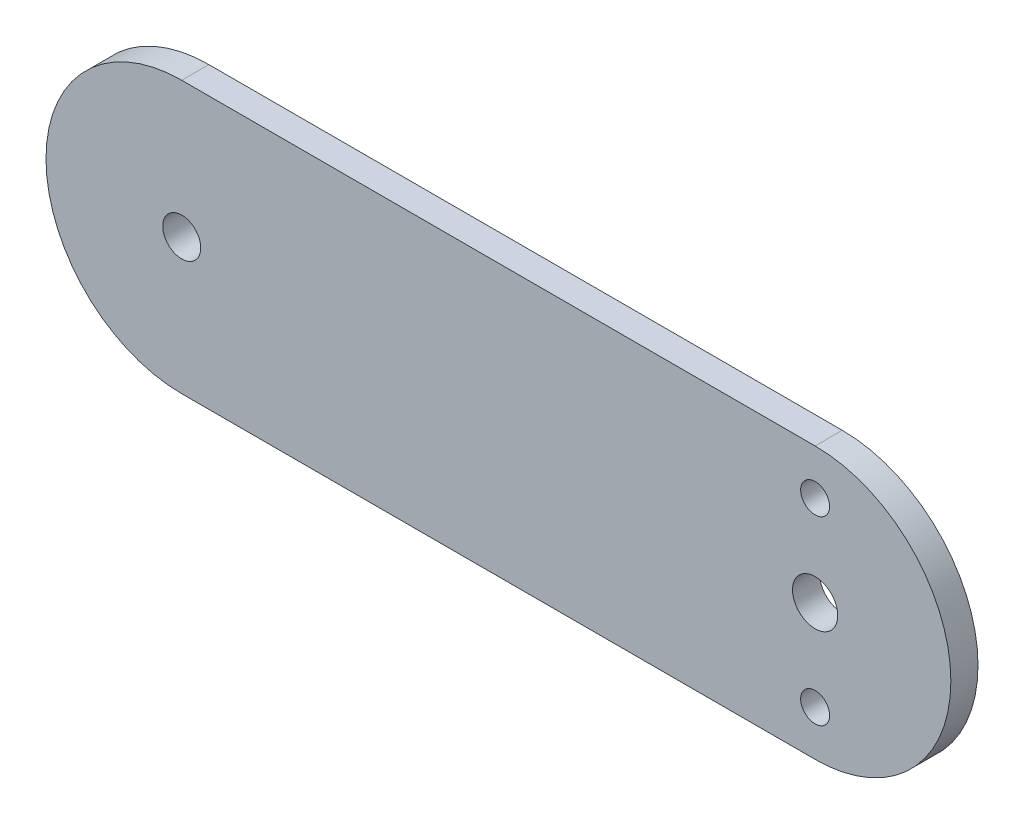
SolidWorks part; units mm, degrees
ref_plane "Plan de face" through (0, 0, 0) normal (0, 0, 1) x (1, 0, 0)
ref_plane "Plan de dessus" through (0, 0, 0) normal (0, 1, 0) x (1, 0, 0)
ref_plane "Plan de droite" through (0, 0, 0) normal (1, 0, 0) x (0, 0, -1)
sketch "Esquisse1" plane through (0, 0, 0) normal (0, 0, 1) x (1, 0, 0)
  line L0 (-35, 15) -> (35, 15)
  line L1 (-35, -15) -> (35, -15)
  line L2 (0, -15) -> (0, 25.8382) construction
  arc A0 (35, 15) -> (35, -15) centre (35, 0) cw
  circle A1 centre (35, 0) radius 2.5
  arc A3 (-35, 15) -> (-35, -15) centre (-35, 0) ccw
  circle A4 centre (-35, 0) radius 2.1
  dimension "D4" = 5
  dimension "D5" = 4.2
  dimension "D1" = 35
  dimension "D2" = 15
  dimension "D3" = 30
extrude "Boss.-Extru.1" add sketch "Esquisse1" along normal blind 3
sketch "Esquisse2" plane through (0, 0, 3) normal (0, 0, 1) x (1, 0, 0)
  line L0 (27.4193, 0) -> (44.4386, 0) construction
  line L1 (35, 15) -> (35, -17.3087) construction
  arc A0 (35, -15) -> (35, 15) centre (35, 0) ccw construction
  circle A1 centre (35, 10) radius 1.6
  circle A2 centre (35, -10) radius 1.6
  dimension "D1" = 3.2
  dimension "D2" = 10
extrude "Enlèv. mat.-Extru.1" cut sketch "Esquisse2" against normal through all
